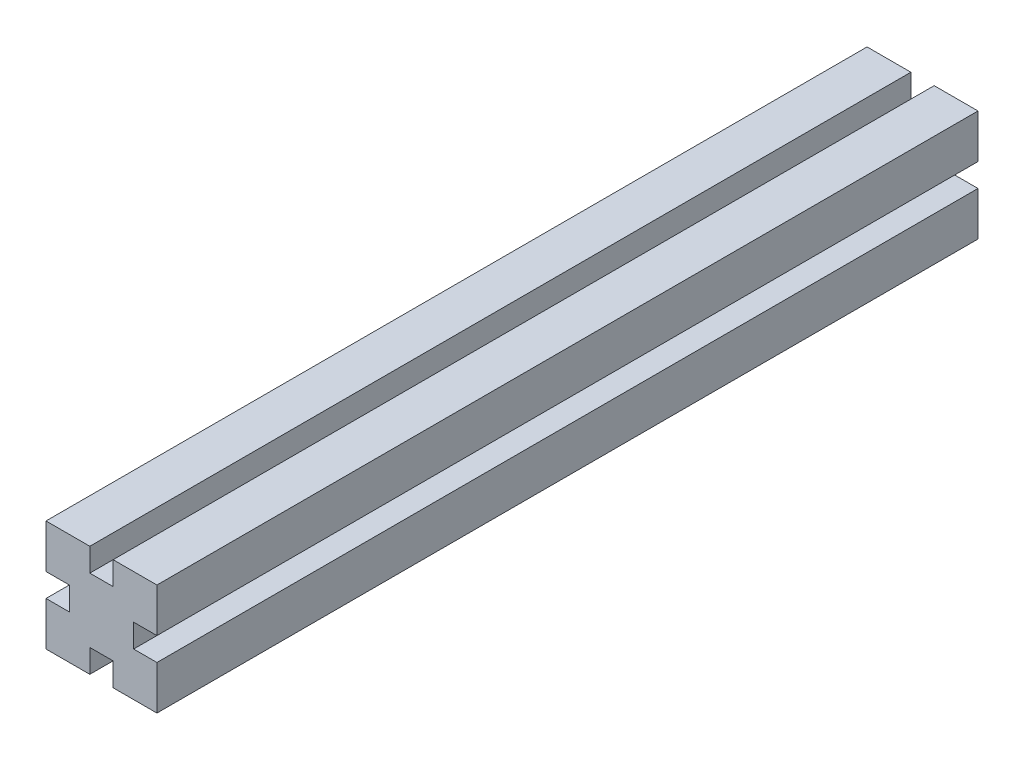
SolidWorks part; units mm, degrees
ref_plane "Front Plane" through (0, 0, 0) normal (0, 0, 1) x (1, 0, 0)
ref_plane "Top Plane" through (0, 0, 0) normal (0, 1, 0) x (1, 0, 0)
ref_plane "Right Plane" through (0, 0, 0) normal (1, 0, 0) x (0, 0, -1)
sketch "Sketch1" plane through (0, 0, 0) normal (0, 0, 1) x (1, 0, 0)
  line L0 (-19.05, -19.05) -> (-4, -19.05)
  line L1 (-4, -19.05) -> (-4, -11.05)
  line L2 (-4, -11.05) -> (4, -11.05)
  line L3 (4, -11.05) -> (4, -19.05)
  line L4 (4, -19.05) -> (19.05, -19.05)
  line L5 (19.05, -19.05) -> (19.05, -4)
  line L6 (19.05, -4) -> (11.05, -4)
  line L7 (11.05, -4) -> (11.05, 4)
  line L8 (11.05, 4) -> (19.05, 4)
  line L9 (19.05, 4) -> (19.05, 19.05)
  line L10 (19.05, 19.05) -> (4, 19.05)
  line L11 (4, 19.05) -> (4, 11.05)
  line L12 (4, 11.05) -> (-4, 11.05)
  line L13 (-4, 11.05) -> (-4, 19.05)
  line L14 (-4, 19.05) -> (-19.05, 19.05)
  line L15 (-19.05, 19.05) -> (-19.05, 4)
  line L16 (-19.05, 4) -> (-11.05, 4)
  line L17 (-11.05, 4) -> (-11.05, -4)
  line L18 (-11.05, -4) -> (-19.05, -4)
  line L19 (-19.05, -4) -> (-19.05, -19.05)
extrude "Profile" add sketch "Sketch1" along normal blind 282
equation "\"length\" = 282.0mm"
